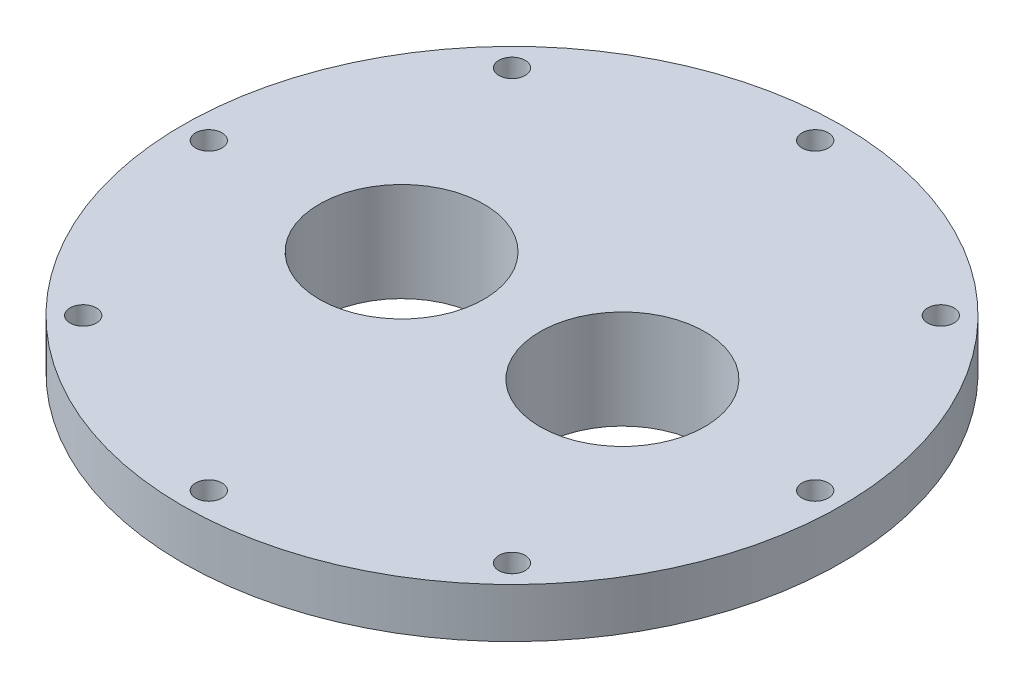
SolidWorks part; units mm, degrees
ref_plane "Front Plane" through (0, 0, 0) normal (0, 0, 1) x (1, 0, 0)
ref_plane "Top Plane" through (0, 0, 0) normal (0, 1, 0) x (1, 0, 0)
ref_plane "Right Plane" through (0, 0, 0) normal (1, 0, 0) x (0, 0, -1)
sketch "Sketch1" plane through (0, 0, 0) normal (0, 1, 0) x (1, 0, 0)
  line L0 (0, 67) -> (0, -67)
  line L1 (0, 0) -> (-67, 0)
  line L3 (0, 0) -> (3.3637, 0)
  circle A0 centre (0, 0) radius 67
  circle A1 centre (-33.5, 0) radius 25
  circle A2 centre (33.5, 0) radius 25
  point P16 (0, -25)
  dimension "D1" = 134
  dimension "D2" = 50
extrude "Boss-Extrude1" add sketch "Sketch1" along normal blind 15
sketch "Sketch2" plane through (0, 15, 0) normal (0, 1, 0) x (1, 0, 0)
  line L0 (33.5, 0) -> (0, 0)
  line L1 (0, 0) -> (-33.5, 0)
  circle A0 centre (0, 0) radius 100
  circle A1 centre (33.5, 0) radius 25
  circle A2 centre (-33.5, 0) radius 25
  circle A3 centre (33.5, 0) radius 25 construction
  circle A4 centre (-33.5, 0) radius 25 construction
  dimension "D1" = 200
extrude "Boss-Extrude2" add sketch "Sketch2" along normal blind 15
sketch "Sketch4" plane through (0, 30, 0) normal (0, 1, 0) x (1, 0, 0)
  line L0 (0, 0) -> (-92, 0)
  circle A0 centre (-92, 0) radius 4
  dimension "D2" = 8
  dimension "D1" = 92
extrude "Cut-Extrude2" cut sketch "Sketch4" against normal blind 15 contours A0
pattern_circular "CirPattern1" count 8 every 45 about axis through (0, 0, 0) along (0, 1, 0) of "Cut-Extrude2"
